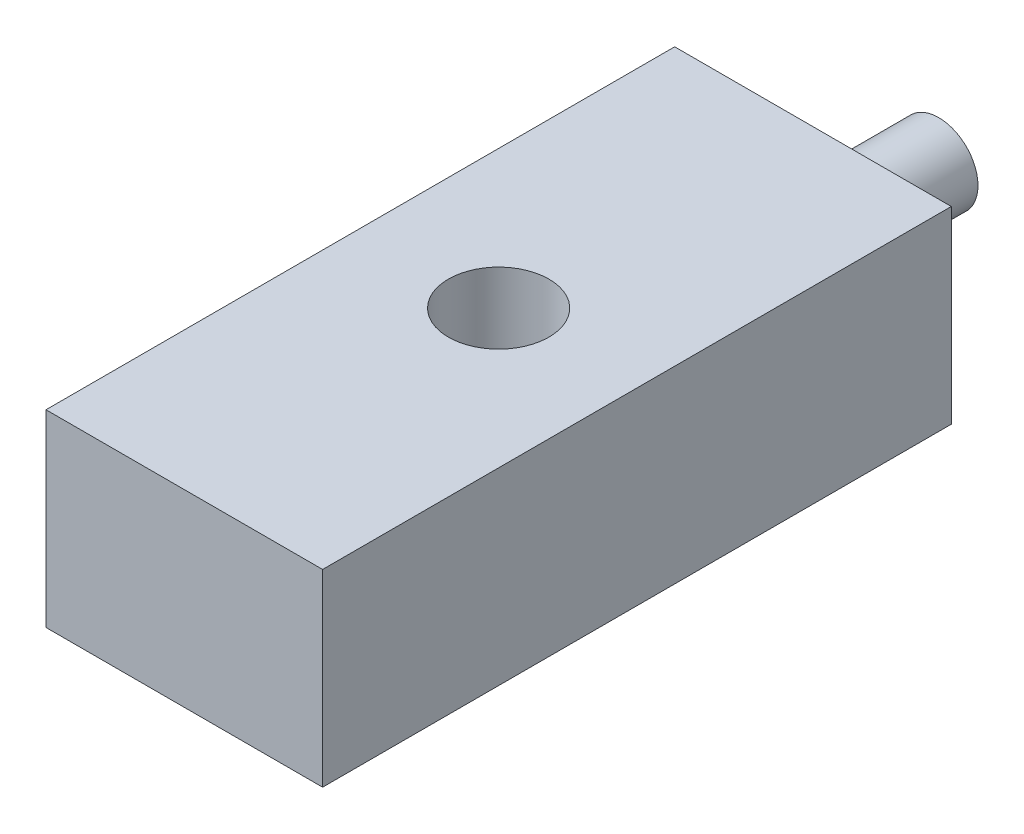
SolidWorks part; units mm, degrees
ref_plane "Alzado" through (0, 0, 0) normal (0, 0, 1) x (1, 0, 0)
ref_plane "Planta" through (0, 0, 0) normal (0, 1, 0) x (1, 0, 0)
ref_plane "Vista lateral" through (0, 0, 0) normal (1, 0, 0) x (0, 0, -1)
sketch "Croquis1" plane through (0, 0, 0) normal (0, 0, 1) x (1, 0, 0)
  circle A0 centre (0.1401, 8.0393) radius 3.125
  circle A1 centre (0.1401, 8.0393) radius 2.7
  circle A2 centre (0.1401, 8.0393) radius 3.125 construction
extrude "Saliente-Extruir1" add sketch "Croquis1" along normal blind 10 contours A0 | A1
sketch "Croquis2" plane through (0, 0, 10) normal (0, 0, 1) x (1, 0, 0)
  line L1 (11.1401, 0.5393) -> (-10.8599, 0.5393)
  line L2 (11.1401, 0.5393) -> (11.1401, 15.5393)
  line L3 (11.1401, 15.5393) -> (-10.8599, 15.5393)
  line L4 (-10.8599, 0.5393) -> (-10.8599, 15.5393)
  line L5 (11.1401, 0.5393) -> (-10.8599, 15.5393) construction
  line L6 (11.1401, 15.5393) -> (-10.8599, 0.5393) construction
  point P0 (0.1401, 8.0393)
  dimension "D1" = 15
  dimension "D2" = 22
extrude "Saliente-Extruir2" add sketch "Croquis2" along normal blind 50
sketch "Croquis3" plane through (0, 0.5393, 0) normal (0, -1, 0) x (1, 0, 0)
  line L0 (0.1401, 10) -> (0.1401, 35) construction
  line L1 (-10.8599, 10) -> (11.1401, 10) construction
  line L2 (0.1401, 35) -> (-10.8599, 35) construction
  line L3 (-10.8599, 60) -> (-10.8599, 10) construction
  circle A0 centre (0.1401, 35) radius 4
  dimension "D1" = 8
extrude "Cortar-Extruir1" cut sketch "Croquis3" against normal through all
